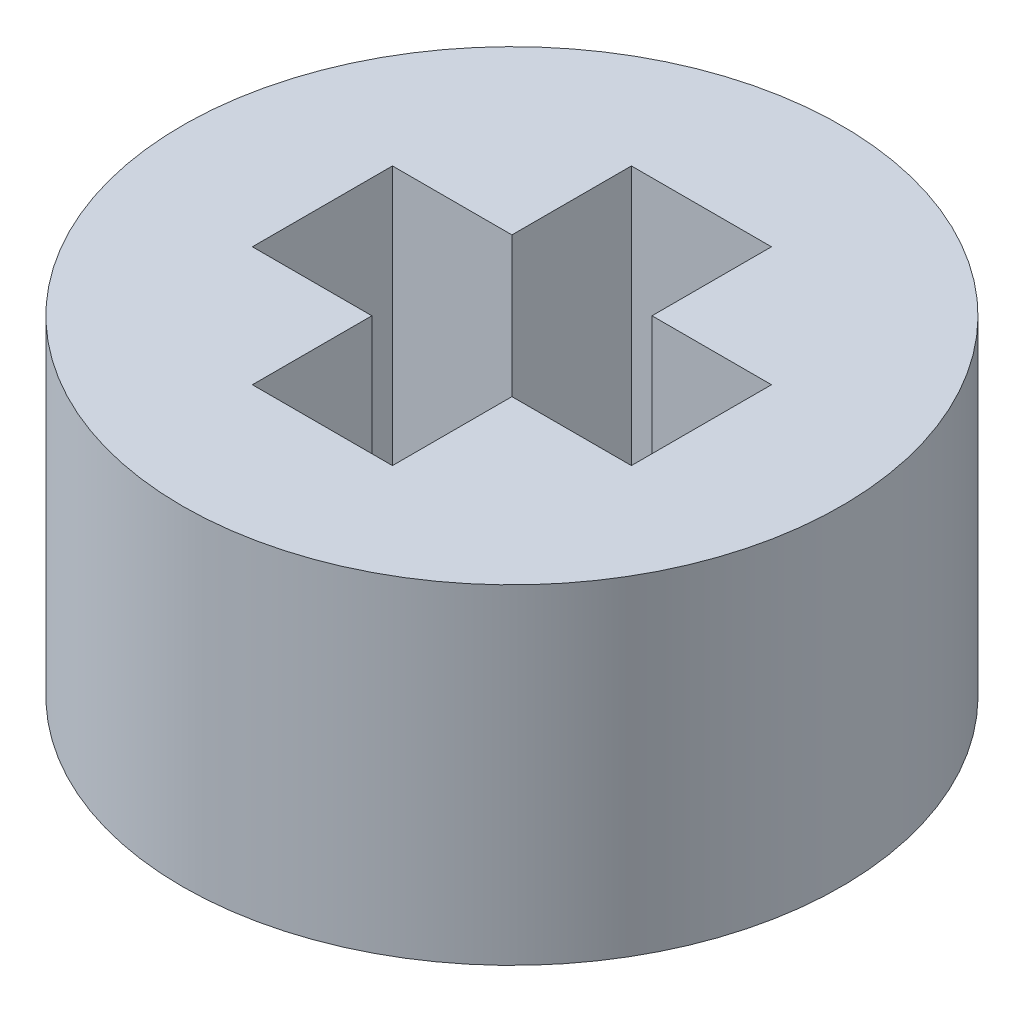
SolidWorks part; units mm, degrees
ref_plane "Front Plane" through (0, 0, 0) normal (0, 0, 1) x (1, 0, 0)
ref_plane "Top Plane" through (0, 0, 0) normal (0, 1, 0) x (1, 0, 0)
ref_plane "Right Plane" through (0, 0, 0) normal (1, 0, 0) x (0, 0, -1)
sketch "Sketch2" plane through (0, 0, 0) normal (0, 1, 0) x (1, 0, 0)
  line L0 (0.85, 0.85) -> (2.3, 0.85)
  line L1 (-0.85, 2.3) -> (0.85, 2.3)
  line L2 (-0.85, 2.3) -> (-0.85, 0.85)
  line L3 (-0.85, -2.3) -> (0.85, -2.3)
  line L4 (0.85, 2.3) -> (0.85, 0.85)
  line L7 (-2.3, 0.85) -> (-0.85, 0.85)
  line L8 (-2.3, 0.85) -> (-2.3, -0.85)
  line L9 (-2.3, -0.85) -> (-0.85, -0.85)
  line L10 (2.3, 0.85) -> (2.3, -0.85)
  line L14 (-0.85, -0.85) -> (-0.85, -2.3)
  line L16 (0.85, -0.85) -> (2.3, -0.85)
  line L17 (0.85, -0.85) -> (0.85, -2.3)
  circle A0 centre (0, 0) radius 4
  point P0 (0, 0)
  point P6 (0, 0)
  dimension "D5" = 8
  dimension "D1" = 1.7
  dimension "D2" = 1.7
  dimension "D3" = 4.6
  dimension "D4" = 4.6
extrude "Boss-Extrude1" add sketch "Sketch2" along normal blind 4
